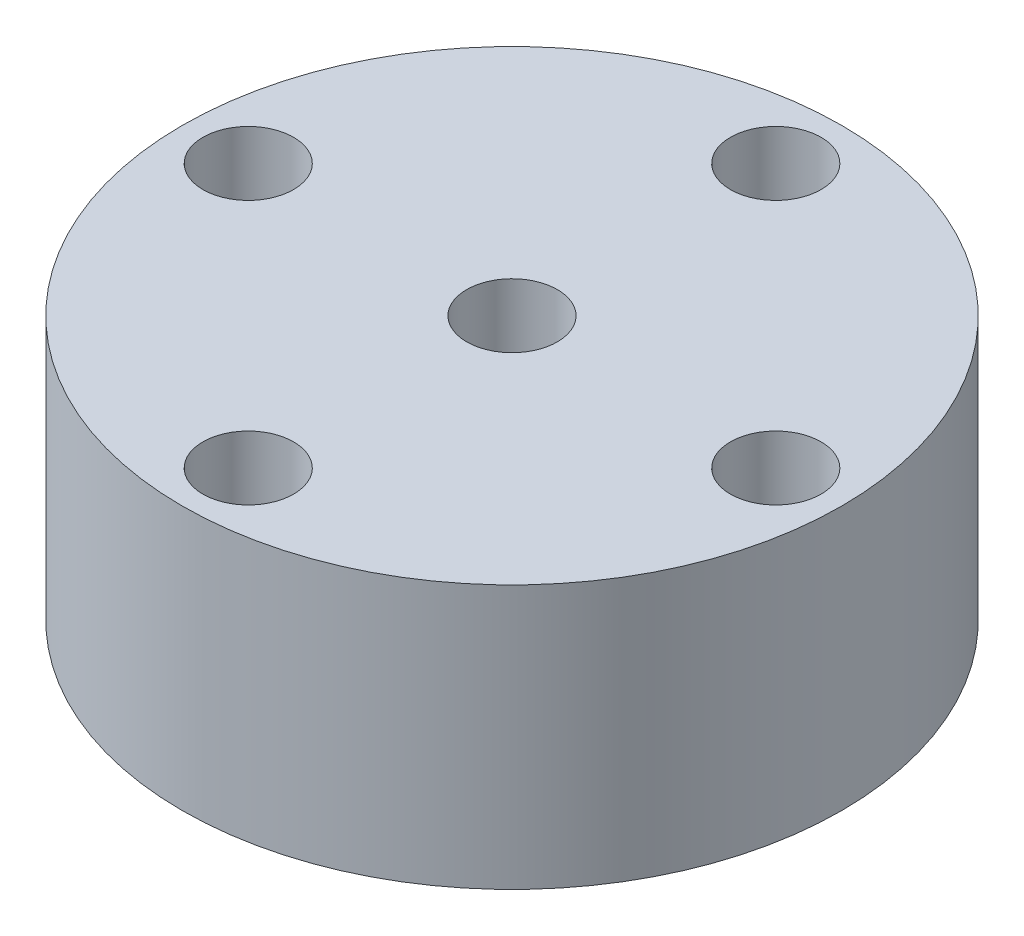
SolidWorks part; units mm, degrees
ref_plane "Front Plane" through (0, 0, 0) normal (0, 0, 1) x (1, 0, 0)
ref_plane "Top Plane" through (0, 0, 0) normal (0, 1, 0) x (1, 0, 0)
ref_plane "Right Plane" through (0, 0, 0) normal (1, 0, 0) x (0, 0, -1)
sketch "Sketch1" plane through (0, 0, 0) normal (0, 1, 0) x (1, 0, 0)
  circle A0 centre (0, 0) radius 2.1828
  circle A1 centre (12.7, 0) radius 2.1828
  circle A2 centre (-12.7, 0) radius 2.1828
  circle A3 centre (0, 0) radius 15.875
  circle A4 centre (0, 12.7) radius 2.1828
  circle A5 centre (0, -12.7) radius 2.1828
  dimension "D3" = 4.3656
  dimension "D4" = 4.3656
  dimension "D5" = 4.3656
  dimension "D6" = 31.75
  dimension "D9" = 4.3656
  dimension "D10" = 4.3656
  dimension "D1" = 12.7
  dimension "D2" = 12.7
  dimension "D7" = 12.7
  dimension "D8" = 12.7
extrude "Boss-Extrude1" add sketch "Sketch1" along normal blind 12.7
